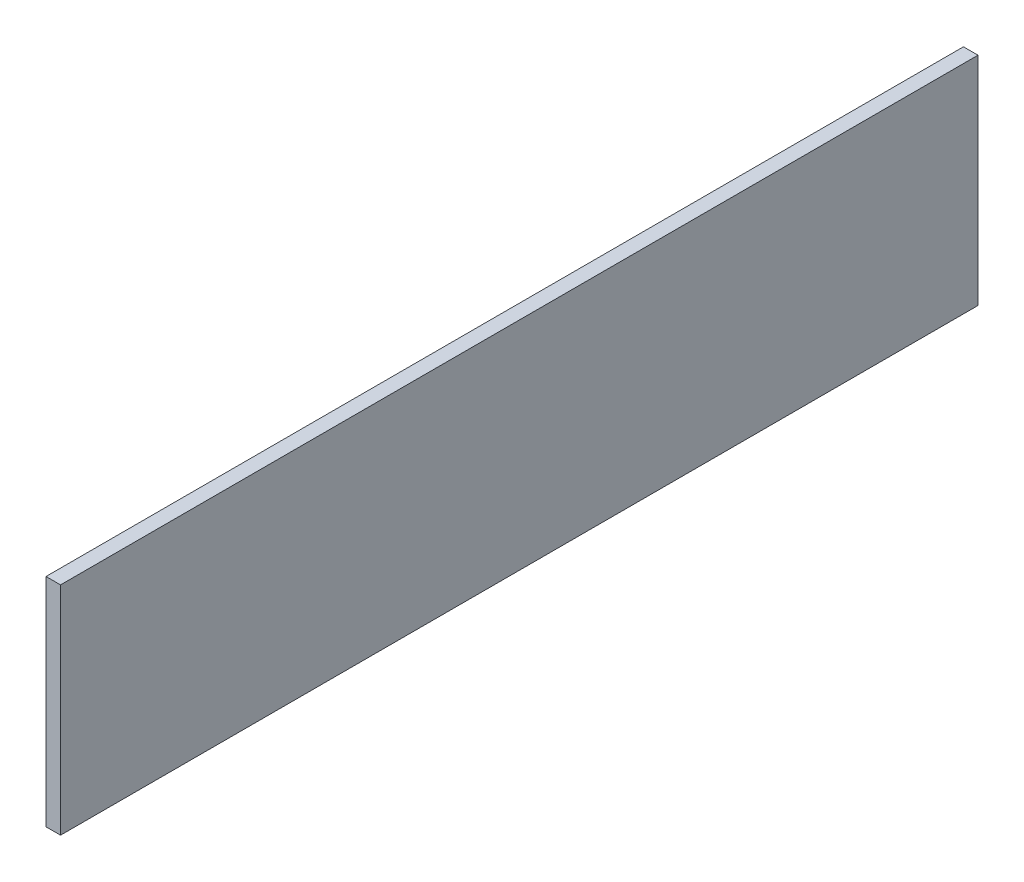
SolidWorks part; units mm, degrees
ref_plane "Front Plane" through (0, 0, 0) normal (0, 0, 1) x (1, 0, 0)
ref_plane "Top Plane" through (0, 0, 0) normal (0, 1, 0) x (1, 0, 0)
ref_plane "Right Plane" through (0, 0, 0) normal (1, 0, 0) x (0, 0, -1)
other "Configuration Table"
sketch "Sketch1" plane through (0, 0, 0) normal (0, 0, 1) x (1, 0, 0)
  line L1 (702, 1469) -> (714, 1469)
  line L2 (702, 1469) -> (702, 1648)
  line L3 (702, 1648) -> (714, 1648)
  line L4 (714, 1469) -> (714, 1648)
extrude "DET2_bolme_saci_sol_1" add sketch "Sketch1" against normal blind 757.5 separate body
